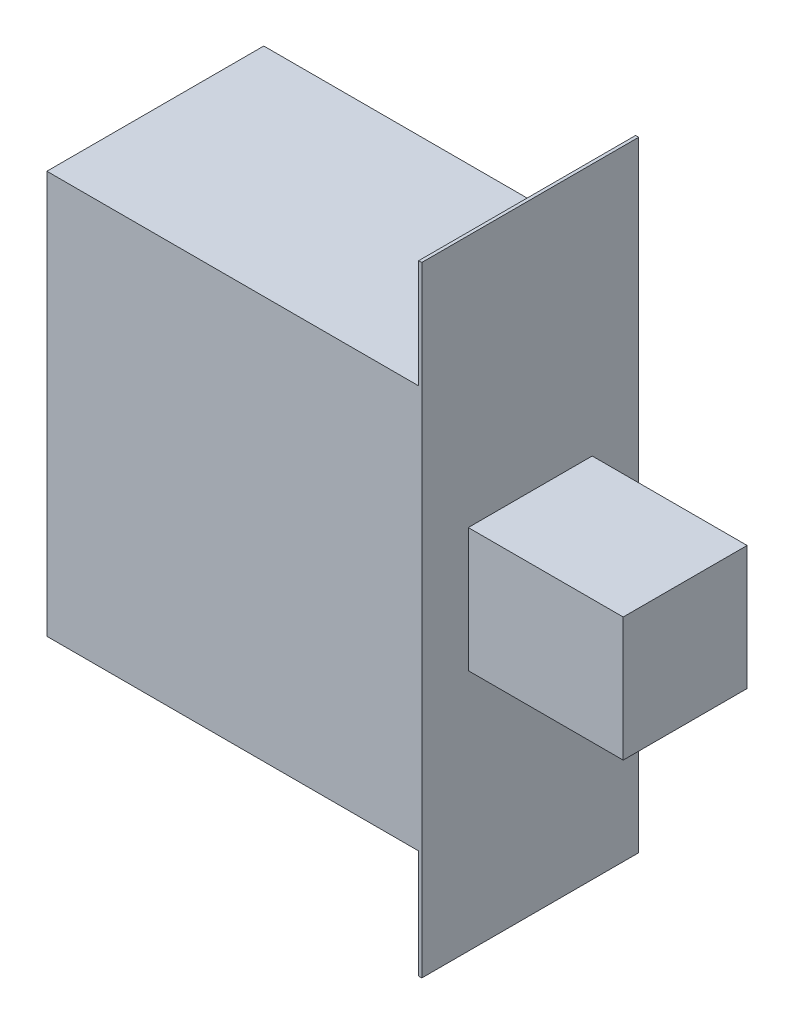
SolidWorks part; units mm, degrees
ref_plane "Front Plane" through (0, 0, 0) normal (0, 0, 1) x (1, 0, 0)
ref_plane "Top Plane" through (0, 0, 0) normal (0, 1, 0) x (1, 0, 0)
ref_plane "Right Plane" through (0, 0, 0) normal (1, 0, 0) x (0, 0, -1)
sketch "Sketch1" plane through (0, 0, 0) normal (0, 0, 1) x (1, 0, 0)
  line L1 (0, 0) -> (12, 0)
  line L2 (0, 0) -> (0, 13)
  line L3 (0, 13) -> (12, 13)
  line L4 (12, 0) -> (12, 13)
  dimension "D1" = 13
  dimension "D2" = 12
extrude "Boss-Extrude1" add sketch "Sketch1" along normal blind 7
sketch "Sketch3" plane through (12, 0, 0) normal (1, 0, 0) x (0, 0, -1)
  line L0 (-7, 0) -> (-7, 13) construction
  line L1 (-7, 16.5) -> (0, 16.5)
  line L2 (-7, 16.5) -> (-7, -3.5)
  line L3 (-7, -3.5) -> (0, -3.5)
  line L4 (0, 16.5) -> (0, -3.5)
  line L5 (0, 0) -> (0, 13) construction
  line L6 (-7, 13) -> (0, 13) construction
  dimension "D1" = 20
  dimension "D2" = 3.5
extrude "Boss-Extrude2" add sketch "Sketch3" along normal blind 0.1
sketch "Sketch4" plane through (12.1, 0, 0) normal (1, 0, 0) x (0, 0, -1)
  line L0 (-3.5, 16.5) -> (-3.5, -3.5) construction
  line L1 (-5.5, 8.3403) -> (-1.5, 8.3403)
  line L2 (-5.5, 8.3403) -> (-5.5, 4.3403)
  line L3 (-5.5, 4.3403) -> (-1.5, 4.3403)
  line L4 (-1.5, 8.3403) -> (-1.5, 4.3403)
  line L5 (0, 16.5) -> (-7, 16.5) construction
  line L6 (-7, -3.5) -> (0, -3.5) construction
  dimension "D1" = 4
  dimension "D2" = 4
extrude "Boss-Extrude3" add sketch "Sketch4" along normal blind 5
